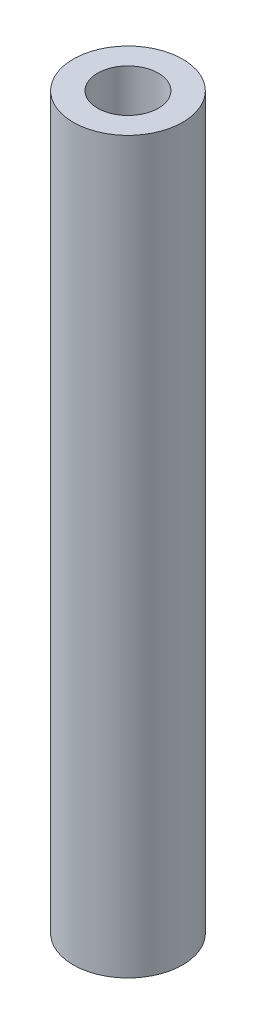
SolidWorks part; units mm, degrees
material "2.1016 (CuSn4)"
ref_plane "前视基准面" through (0, 0, 0) normal (0, 0, 1) x (1, 0, 0)
ref_plane "上视基准面" through (0, 0, 0) normal (0, 1, 0) x (1, 0, 0)
ref_plane "右视基准面" through (0, 0, 0) normal (1, 0, 0) x (0, 0, -1)
other "Configuration Table"
sketch "草图1" plane through (0, 0, 0) normal (0, 1, 0) x (1, 0, 0)
  circle A0 centre (0, 0) radius 2.25
  circle A1 centre (0, 0) radius 1.25
  dimension "D1" = 2.5
  dimension "D2" = 4.5
extrude "凸台-拉伸1" add sketch "草图1" along normal blind 30
